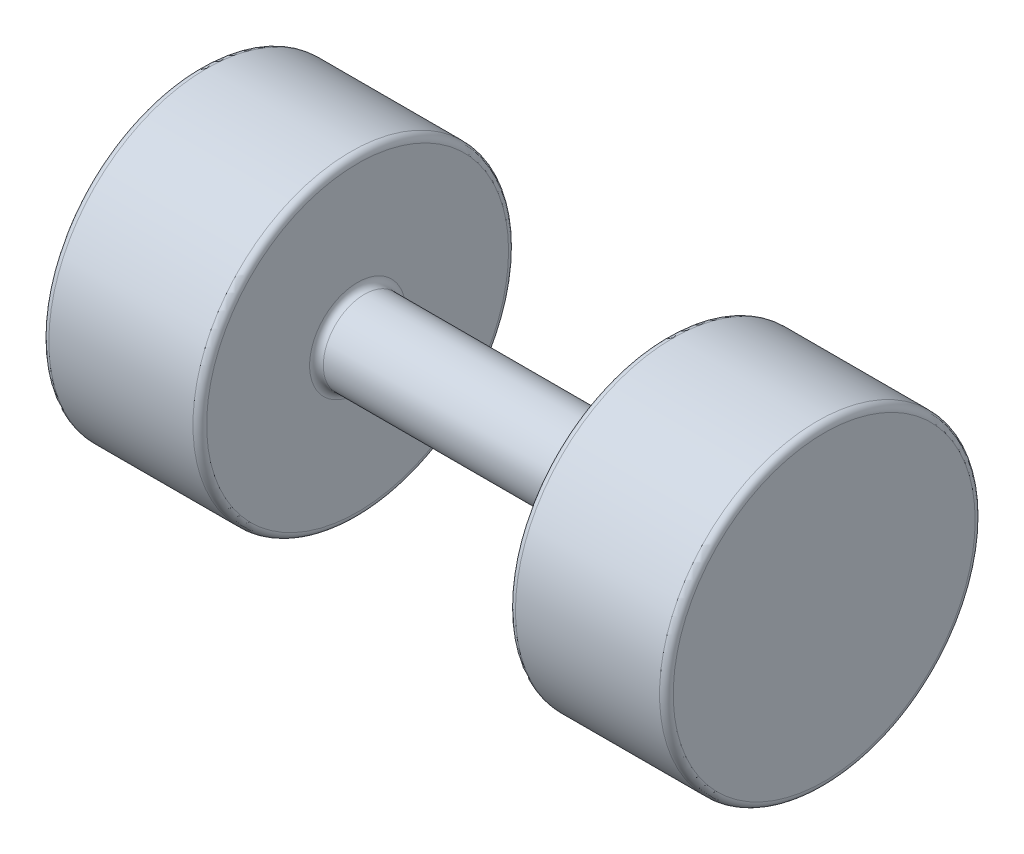
SolidWorks part; units mm, degrees
material "Plain Carbon Steel"
ref_plane "Front Plane" through (0, 0, 0) normal (0, 0, 1) x (1, 0, 0)
ref_plane "Top Plane" through (0, 0, 0) normal (0, 1, 0) x (1, 0, 0)
ref_plane "Right Plane" through (0, 0, 0) normal (1, 0, 0) x (0, 0, -1)
sketch "Sketch1" plane through (0, 0, 0) normal (0, 0, 1) x (1, 0, 0)
  line L0 (-83.0412, 0) -> (0, 0) construction
  line L1 (91, 0) -> (-91, 0)
  line L2 (-91, 0) -> (-91, 46)
  line L3 (-91, 46) -> (-45, 46)
  line L4 (-45, 46) -> (-45, 12)
  line L5 (-45, 12) -> (45, 12)
  line L6 (0, 0) -> (0, 12) construction
  line L7 (91, 0) -> (91, 46)
  line L8 (91, 46) -> (45, 46)
  line L9 (45, 46) -> (45, 12)
  dimension "D1" = 92
  dimension "D2" = 46
  dimension "D3" = 90
  dimension "D4" = 12
revolve "Revolve1" add sketch "Sketch1" angle 360 about L1
fillet "Fillet1" radius 2 6 edges at (91, 0, -46) (45, 0, -46) (-45, 0, -46) (-91, 0, -46) (45, 0, -12) (-45, 0, -12)
